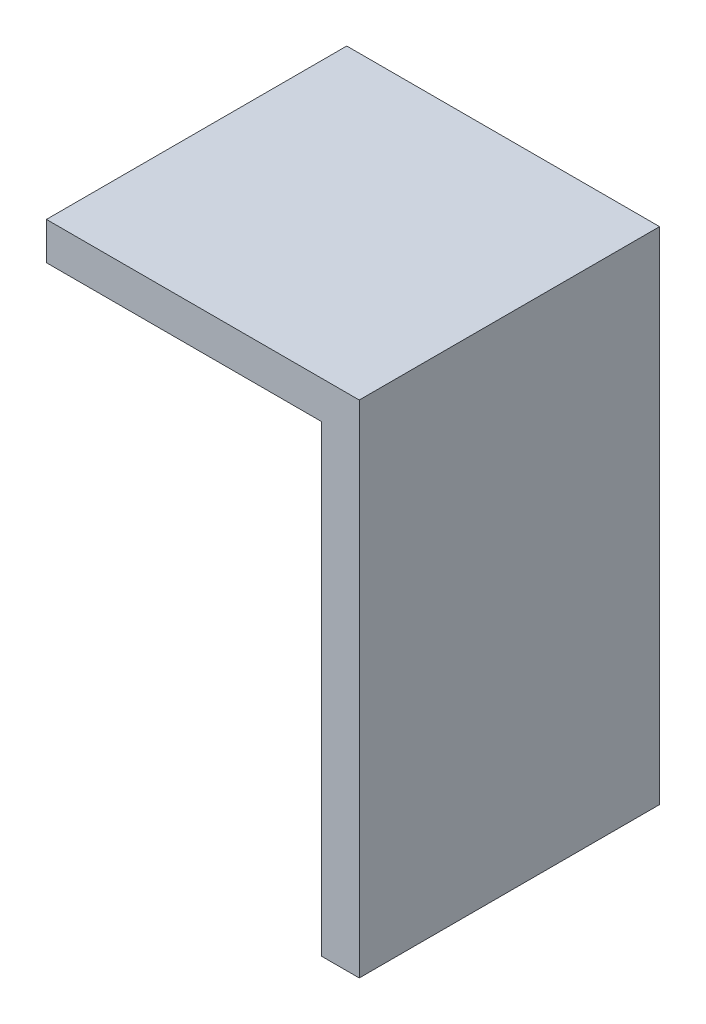
SolidWorks part; units mm, degrees
ref_plane "Front Plane" through (0, 0, 0) normal (0, 0, 1) x (1, 0, 0)
ref_plane "Top Plane" through (0, 0, 0) normal (0, 1, 0) x (1, 0, 0)
ref_plane "Right Plane" through (0, 0, 0) normal (1, 0, 0) x (0, 0, -1)
sketch "SK_P01_Contacttopleg" plane through (0, 0, 0) normal (0, 1, 0) x (1, 0, 0)
  line L0 (-12.5, -12) -> (12.5, -12)
  line L1 (12.5, -12) -> (12.5, 12)
  line L2 (12.5, 12) -> (-12.5, 12)
  line L3 (-12.5, 12) -> (-12.5, -12)
extrude "P01_Contacttopleg" add sketch "SK_P01_Contacttopleg" along normal blind 3 from offset 37
sketch "SK_P02_Contactface" plane through (0, 0, 0) normal (0, 1, 0) x (1, 0, 0)
  line L0 (9.5, -12) -> (12.5, -12)
  line L1 (12.5, -12) -> (12.5, 12)
  line L2 (12.5, 12) -> (9.5, 12)
  line L3 (9.5, 12) -> (9.5, -12)
extrude "P02_Contactface" add sketch "SK_P02_Contactface" along normal blind 37
